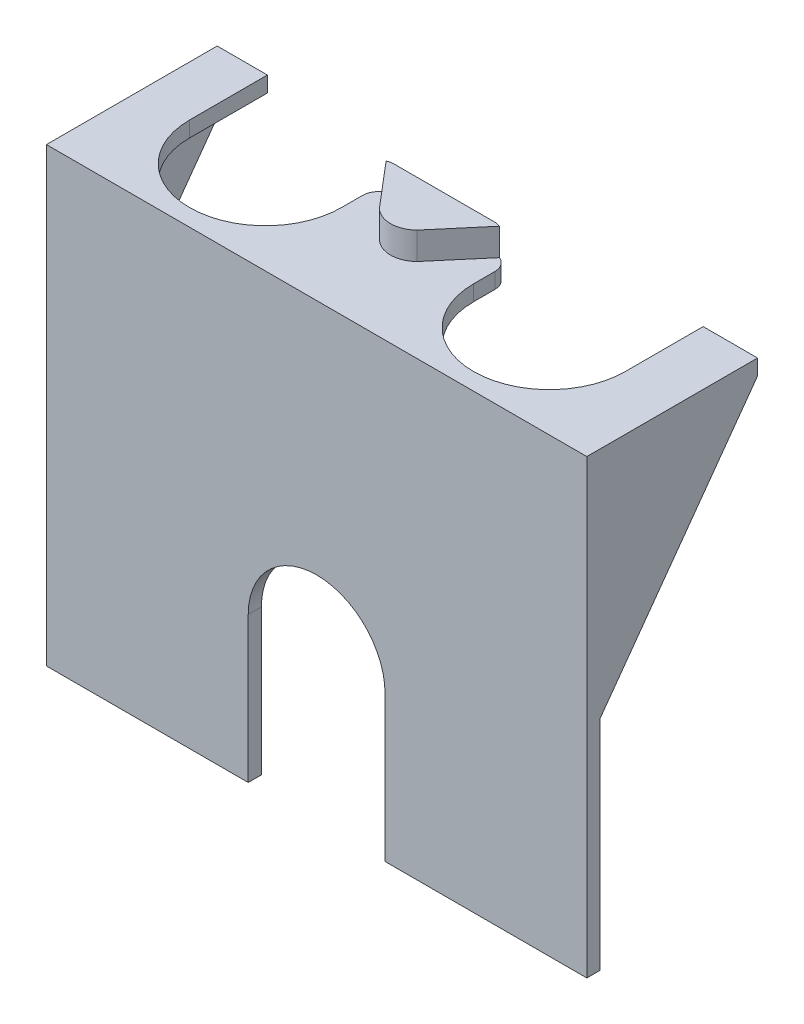
SolidWorks part; units mm, degrees
ref_plane "Front Plane" through (0, 0, 0) normal (0, 0, 1) x (1, 0, 0)
ref_plane "Top Plane" through (0, 0, 0) normal (0, 1, 0) x (1, 0, 0)
ref_plane "Right Plane" through (0, 0, 0) normal (1, 0, 0) x (0, 0, -1)
sketch "Sketch1" plane through (0, 0, 0) normal (0, 1, 0) x (1, 0, 0)
  line L1 (0, 0) -> (138.8166, 0)
  line L2 (0, 0) -> (0, 51.7042)
  line L3 (0, 51.7042) -> (138.8166, 51.7042)
  line L4 (138.8166, 0) -> (138.8166, 51.7042)
extrude "Boss-Extrude1" add sketch "Sketch1" along normal blind 4
sketch "Sketch2" plane through (0, 4, 0) normal (0, 1, 0) x (1, 0, 0)
  circle A0 centre (32.4087, 26.1853) radius 19.5
  circle A1 centre (105.3378, 26.1853) radius 19.5
extrude "Cut-Extrude1" cut sketch "Sketch2" against normal blind 4
sketch "Sketch3" plane through (0, 4, 0) normal (0, 1, 0) x (1, 0, 0)
  line L0 (12.9087, 26.1853) -> (12.9087, 51.7042)
  line L1 (138.8166, 51.7042) -> (0, 51.7042) construction
  line L2 (12.9087, 51.7042) -> (51.9087, 51.7042)
  line L3 (51.9087, 51.7042) -> (51.9087, 26.1853)
  line L4 (51.9087, 26.1853) -> (12.9087, 26.1853)
  line L5 (85.8378, 26.1853) -> (85.8378, 51.7042)
  line L6 (85.8378, 51.7042) -> (124.8378, 51.7042)
  line L7 (124.8378, 51.7042) -> (124.8378, 26.1853)
  line L8 (124.8378, 26.1853) -> (85.8378, 26.1853)
  circle A0 centre (32.4087, 26.1853) radius 19.5 construction
  circle A1 centre (105.3378, 26.1853) radius 19.5 construction
extrude "Cut-Extrude2" cut sketch "Sketch3" against normal blind 4
sketch "Sketch4" plane through (0, 4, 0) normal (0, 1, 0) x (1, 0, 0)
  line L0 (0, 51.7042) -> (138.8166, 51.7042)
  line L1 (138.8166, 51.7042) -> (138.8166, 46.1764)
  line L2 (138.8166, 0) -> (138.8166, 51.7042) construction
  line L3 (138.8166, 46.1764) -> (0, 46.1764)
  line L4 (0, 51.7042) -> (0, 0) construction
  line L5 (0, 46.1764) -> (0, 51.7042)
extrude "Cut-Extrude3" cut sketch "Sketch4" against normal blind 4
sketch "Sketch5" plane through (0, 4, 0) normal (0, 1, 0) x (1, 0, 0)
  line L0 (51.9283, 38.3631) -> (49.904, 40.3873)
  line L1 (49.904, 40.3873) -> (49.904, 49.124)
  line L2 (49.904, 49.124) -> (88.9763, 49.124)
  line L3 (88.9763, 49.124) -> (88.231, 41.2978)
  line L4 (85.8573, 38.3483) -> (87.9538, 40.8196)
  line L5 (87.9538, 40.8196) -> (88.231, 41.2978)
  line L7 (51.9283, 38.3631) -> (53.3899, 36.6499)
  line L8 (53.3899, 36.6499) -> (84.4166, 36.6499)
  line L9 (84.4166, 36.6499) -> (85.8573, 38.3483)
extrude "Cut-Extrude4" cut sketch "Sketch5" against normal blind 4
sketch "Sketch6" plane through (0, 4, 0) normal (0, 1, 0) x (1, 0, 0)
  line L2 (53.2701, 36.4725) -> (84.2967, 36.4725)
  line L3 (84.2967, 36.4725) -> (73.6211, 23.8907)
  line L4 (63.8916, 23.9803) -> (53.2701, 36.4725)
  arc A0 (63.8916, 23.9803) -> (73.6211, 23.8907) centre (68.8011, 28.8002) ccw
extrude "Boss-Extrude2" add sketch "Sketch6" along normal blind 7
sketch "Sketch8" plane through (0, 0, -36.6499) normal (0, 0, -1) x (-1, 0, 0)
  line L1 (-87.5229, -4.1569) -> (-46.3125, -4.1569)
  line L2 (-87.5229, -4.1569) -> (-87.5229, 14.5671)
  line L3 (-87.5229, 14.5671) -> (-46.3125, 14.5671)
  line L4 (-46.3125, -4.1569) -> (-46.3125, 14.5671)
extrude "Cut-Extrude6" cut sketch "Sketch8" against normal blind 1 and the other way blind 10
fillet "Fillet1" radius 4 2 edges at (85.8378, 2, -35.6499) (51.9087, 2, -35.6499)
sketch "Sketch9" plane through (0, 4, 0) normal (0, 1, 0) x (1, 0, 0)
  line L1 (-8.5571, -5.8989) -> (150.7055, -5.8989)
  line L2 (-8.5571, -5.8989) -> (-8.5571, 2.3196)
  line L3 (-8.5571, 2.3196) -> (150.7055, 2.3196)
  line L4 (150.7055, -5.8989) -> (150.7055, 2.3196)
extrude "Cut-Extrude7" cut sketch "Sketch9" against normal blind 13
sketch "Sketch10" plane through (0, 0, 0) normal (0, -1, 0) x (-1, 0, 0)
  line L0 (-138.8166, 2.3196) -> (-138.8166, 46.1764) construction
  line L1 (0, 2.3196) -> (-138.8166, 2.3196)
  line L2 (0, 2.3196) -> (0, 5.7007)
  line L3 (0, 5.7007) -> (-138.8166, 5.7007)
  line L4 (-138.8166, 2.3196) -> (-138.8166, 5.7007)
extrude "Boss-Extrude3" add sketch "Sketch10" along normal blind 112
sketch "Sketch11" plane through (0, 0, -5.7007) normal (0, 0, -1) x (-1, 0, 0)
  line L1 (0, -112) -> (-138.8166, -112) construction
  line L3 (-51.8339, -74.6081) -> (-51.8339, -112)
  line L4 (-51.8339, -112) -> (-86.9827, -112)
  line L5 (-86.9827, -112) -> (-86.9827, -74.6081)
  arc A0 (-86.9827, -74.6081) -> (-51.8339, -74.6081) centre (-69.4083, -74.6081) cw
  point P7 (-69.4083, -65.9095)
extrude "Cut-Extrude8" cut sketch "Sketch11" against normal blind 6
sketch "Sketch12" plane through (0, 0, 0) normal (-1, 0, 0) x (0, 0, 1)
  line L0 (-46.1764, 0) -> (-5.7007, 0)
  line L1 (-5.7007, 0) -> (-5.7007, -56)
  line L2 (-5.7007, -112) -> (-5.7007, 0) construction
  line L3 (-5.7007, -56) -> (-46.1764, 0)
extrude "Boss-Extrude4" add sketch "Sketch12" against normal blind 5
sketch "Sketch13" plane through (138.8166, 0, 0) normal (1, 0, 0) x (0, 0, -1)
  line L0 (5.7007, 0) -> (46.1764, 0)
  line L1 (46.1764, 0) -> (5.7007, -56)
  line L2 (5.7007, -56) -> (5.7007, 0)
extrude "Boss-Extrude5" add sketch "Sketch13" against normal blind 5
ref_plane "Plane1" through (69, 0, 0) normal (1, 0, 0) x (0, 0, -1)
sketch "Sketch14" plane through (69, 0, 0) normal (1, 0, 0) x (0, 0, -1)
  line L0 (5.7007, 0) -> (35.6499, 0)
  line L1 (5.7007, -56) -> (5.7007, 0) construction
  line L2 (31.6499, 0) -> (35.6499, 0) construction
  line L3 (46.1764, 0) -> (26.1853, 0) construction
  line L4 (35.6499, 0) -> (5.7007, -41.4361)
  line L5 (5.7007, -41.4361) -> (5.7007, 0)
extrude "Boss-Extrude6" add sketch "Sketch14" along normal blind 3 and the other way blind 3
